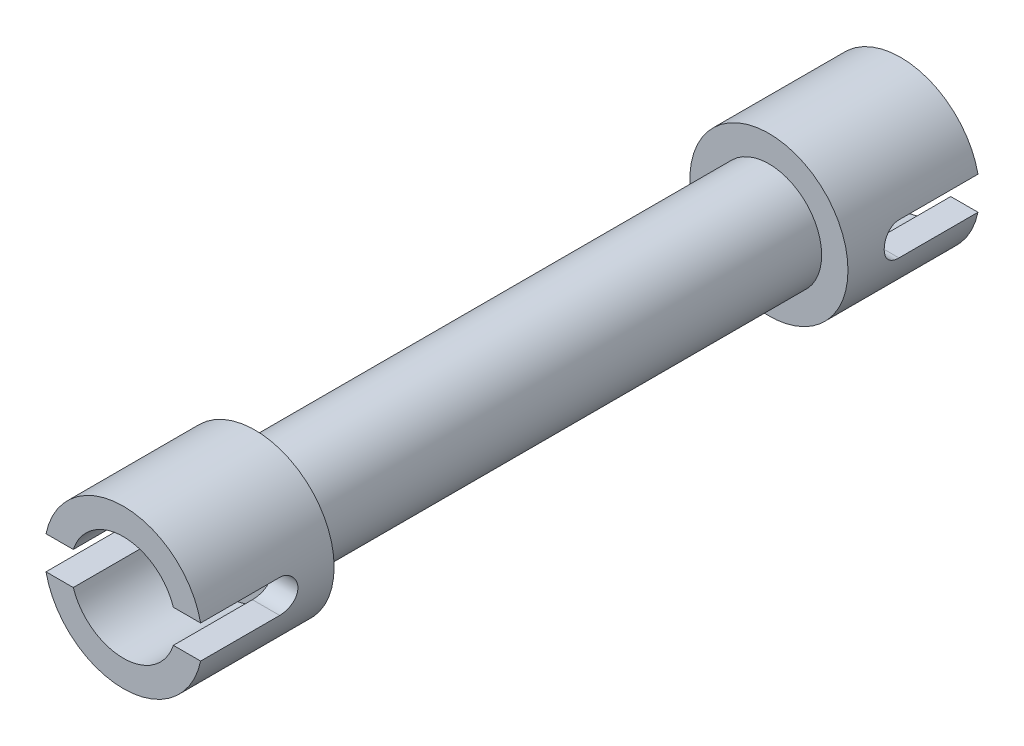
SolidWorks part; units mm, degrees
ref_plane "Alzado" through (0, 0, 0) normal (0, 0, 1) x (1, 0, 0)
ref_plane "Planta" through (0, 0, 0) normal (0, 1, 0) x (1, 0, 0)
ref_plane "Vista lateral" through (0, 0, 0) normal (1, 0, 0) x (0, 0, -1)
sketch "Croquis1" plane through (0, 0, 0) normal (0, 0, 1) x (1, 0, 0)
  circle A0 centre (0, 0) radius 4
  dimension "D1" = 8
extrude "Saliente-Extruir1" add sketch "Croquis1" along normal mid plane 39
sketch "Croquis2" plane through (0, 0, 19.5) normal (0, 0, 1) x (1, 0, 0)
  circle A0 centre (0, 0) radius 6
  dimension "D1" = 12
extrude "Saliente-Extruir2" add sketch "Croquis2" along normal blind 10
sketch "Croquis3" plane through (0, 0, 29.5) normal (0, 0, 1) x (1, 0, 0)
  circle A0 centre (0, 0) radius 4
  dimension "D1" = 8
extrude "Cortar-Extruir1" cut sketch "Croquis3" against normal blind 8
ref_plane "Plano1" through (6, 0, 0) normal (1, 0, 0) x (0, 0, -1)
sketch "Croquis4" plane through (6, 0, 0) normal (1, 0, 0) x (0, 0, -1)
  line L0 (-29.5, 0) -> (-23.5, 0) construction
  line L1 (-29.5, 1.25) -> (-23.5, 1.25)
  line L2 (-29.5, -1.25) -> (-23.5, -1.25)
  line L3 (-29.5, 6) -> (-29.5, -6) construction
  arc A0 (-29.5, 1.25) -> (-29.5, -1.25) centre (-29.5, 0) ccw
  arc A1 (-23.5, -1.25) -> (-23.5, 1.25) centre (-23.5, 0) ccw
  point P3 (-26.5, 0)
  dimension "D1" = 6
  dimension "D2" = 2.5
extrude "Cortar-Extruir2" cut sketch "Croquis4" against normal through all
mirror "Simetría2" about plane through (0, 0, 0) normal (0, 0, 1) of "Saliente-Extruir2", "Cortar-Extruir1", "Cortar-Extruir2"
